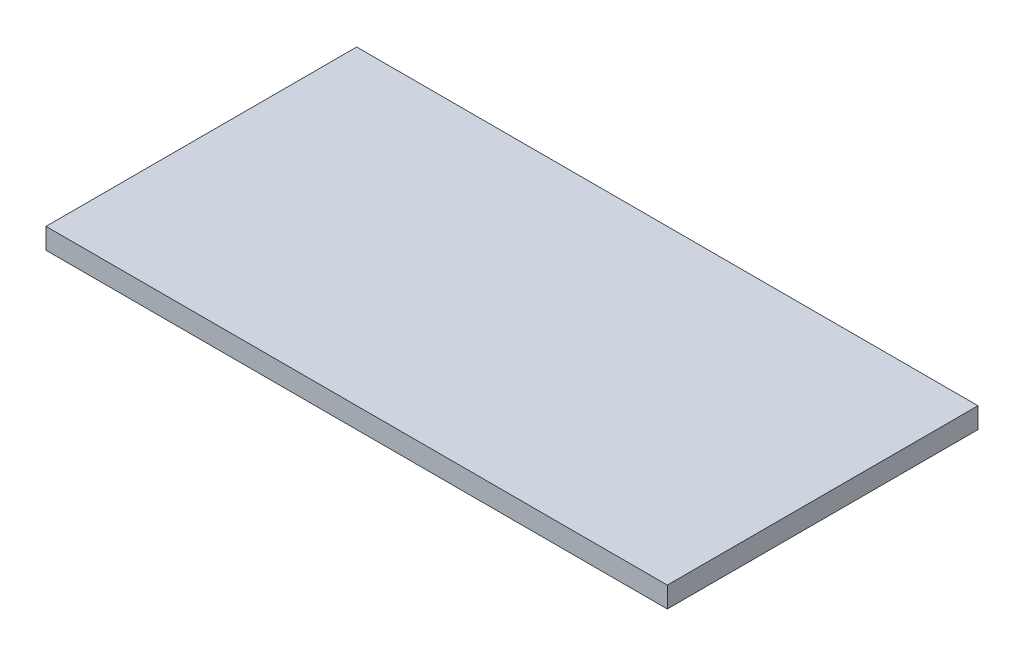
SolidWorks part; units mm, degrees
ref_plane "Front Plane" through (0, 0, 0) normal (0, 0, 1) x (1, 0, 0)
ref_plane "Top Plane" through (0, 0, 0) normal (0, 1, 0) x (1, 0, 0)
ref_plane "Right Plane" through (0, 0, 0) normal (1, 0, 0) x (0, 0, -1)
sketch "Sketch1" plane through (0, 0, 0) normal (0, 1, 0) x (1, 0, 0)
  line L1 (0, 0) -> (60, 0)
  line L2 (0, 0) -> (0, -30)
  line L3 (0, -30) -> (60, -30)
  line L4 (60, 0) -> (60, -30)
  dimension "D1" = 30
  dimension "D2" = 60
extrude "Boss-Extrude1" add sketch "Sketch1" along normal blind 2
